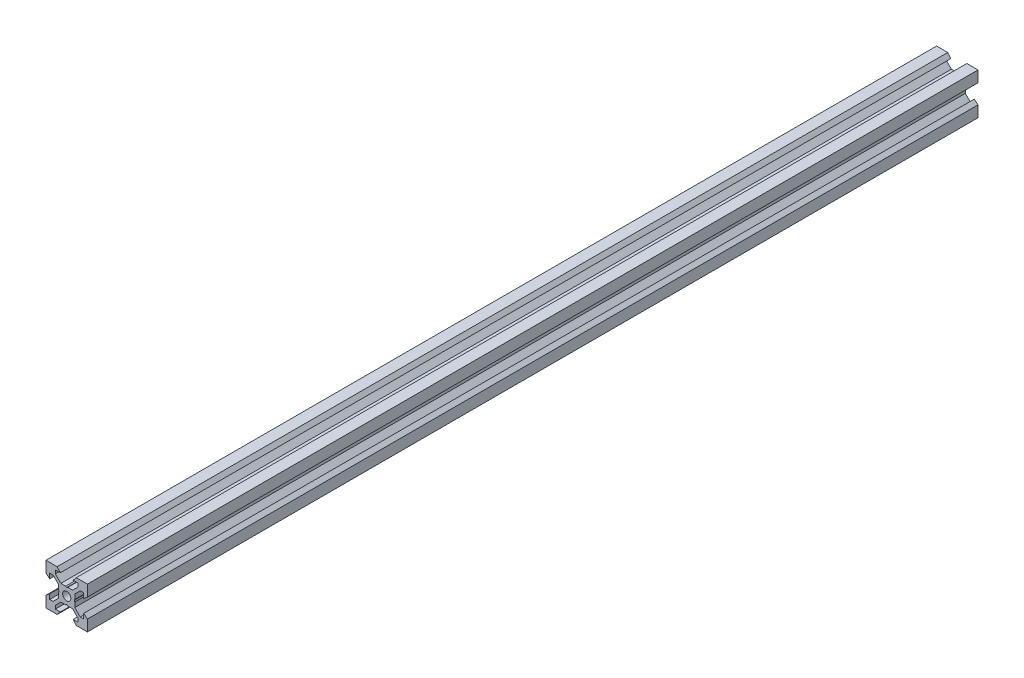
SolidWorks part; units mm, degrees
ref_plane "Front Plane" through (0, 0, 0) normal (0, 0, 1) x (1, 0, 0)
ref_plane "Top Plane" through (0, 0, 0) normal (0, 1, 0) x (1, 0, 0)
ref_plane "Right Plane" through (0, 0, 0) normal (1, 0, 0) x (0, 0, -1)
sketch "Sketch1" plane through (0, 0, 0) normal (0, 0, 1) x (1, 0, 0)
  line L0 (10, 10) -> (4.6104, 10) construction
  line L1 (10, 10) -> (10, 4.6104) construction
  line L2 (10, -10) -> (10, -4.6104) construction
  line L3 (10, -10) -> (4.6104, -10) construction
  line L4 (10, 10) -> (10, 4.6104)
  line L5 (6.5607, 5.5) -> (8.2, 5.5)
  line L6 (5.5, 8.2) -> (5.5, 6.5607)
  line L7 (10, 10) -> (4.6104, 10)
  line L8 (10, 10) -> (10, 4.6104)
  line L9 (6.5607, 5.5) -> (3.9, 2.8393)
  line L10 (5.5, 6.5607) -> (2.8393, 3.9)
  line L11 (10, 4.6104) -> (8.2, 3.1)
  line L12 (4.6104, 10) -> (3.1, 8.2)
  line L13 (8.2, 3.1) -> (8.2, 5.5)
  line L14 (3.1, 8.2) -> (5.5, 8.2)
  line L15 (-6.5607, 5.5) -> (-8.2, 5.5)
  line L16 (6.5607, -5.5) -> (8.2, -5.5)
  line L17 (3.1, -8.2) -> (5.5, -8.2)
  line L18 (8.2, -3.1) -> (8.2, -5.5)
  line L19 (4.6104, -10) -> (3.1, -8.2)
  line L20 (10, -4.6104) -> (8.2, -3.1)
  line L21 (0.5196, -3.9) -> (0, -3.6)
  line L22 (0.5196, 3.9) -> (0, 3.6)
  line L23 (3.6, 0) -> (3.9, -0.5196)
  line L24 (3.9, 0.5196) -> (3.6, 0)
  line L25 (3.9, 0.5196) -> (3.9, 2.8393)
  line L26 (2.8393, 3.9) -> (0.5196, 3.9)
  line L27 (3.9, -2.8393) -> (3.9, -0.5196)
  line L28 (2.8393, -3.9) -> (0.5196, -3.9)
  line L29 (5.5, -6.5607) -> (2.8393, -3.9)
  line L30 (6.5607, -5.5) -> (3.9, -2.8393)
  line L31 (10, -10) -> (10, -4.6104)
  line L32 (10, -10) -> (4.6104, -10)
  line L33 (5.5, -8.2) -> (5.5, -6.5607)
  line L34 (-6.5607, -5.5) -> (-8.2, -5.5)
  line L35 (10, -10) -> (10, -4.6104)
  line L36 (0, 0) -> (0, 8.2) construction
  line L37 (-10, -10) -> (-4.6104, -10) construction
  line L38 (-10, -10) -> (-10, -4.6104) construction
  line L39 (-10, 10) -> (-10, 4.6104) construction
  line L40 (-10, 10) -> (-4.6104, 10) construction
  line L41 (-10, -10) -> (-10, -4.6104)
  line L43 (-5.5, -8.2) -> (-5.5, -6.5607)
  line L44 (-10, -10) -> (-4.6104, -10)
  line L45 (-10, -10) -> (-10, -4.6104)
  line L46 (-6.5607, -5.5) -> (-3.9, -2.8393)
  line L47 (-5.5, -6.5607) -> (-2.8393, -3.9)
  line L48 (-2.8393, -3.9) -> (-0.5196, -3.9)
  line L49 (-3.9, -2.8393) -> (-3.9, -0.5196)
  line L50 (-2.8393, 3.9) -> (-0.5196, 3.9)
  line L51 (-3.9, 0.5196) -> (-3.9, 2.8393)
  line L52 (-3.9, 0.5196) -> (-3.6, 0)
  line L53 (-3.6, 0) -> (-3.9, -0.5196)
  line L54 (-0.5196, 3.9) -> (0, 3.6)
  line L55 (-0.5196, -3.9) -> (0, -3.6)
  line L56 (-10, -4.6104) -> (-8.2, -3.1)
  line L57 (-4.6104, -10) -> (-3.1, -8.2)
  line L58 (-8.2, -3.1) -> (-8.2, -5.5)
  line L59 (-3.1, -8.2) -> (-5.5, -8.2)
  line L60 (-10, -10) -> (10, -10) construction
  line L61 (-10, -10) -> (-10, 10) construction
  line L62 (-3.1, 8.2) -> (-5.5, 8.2)
  line L63 (-8.2, 3.1) -> (-8.2, 5.5)
  line L64 (-4.6104, 10) -> (-3.1, 8.2)
  line L65 (-10, 4.6104) -> (-8.2, 3.1)
  line L66 (-5.5, 6.5607) -> (-2.8393, 3.9)
  line L67 (-6.5607, 5.5) -> (-3.9, 2.8393)
  line L68 (-10, 10) -> (-10, 4.6104)
  line L69 (-10, 10) -> (-4.6104, 10)
  line L70 (-5.5, 8.2) -> (-5.5, 6.5607)
  line L71 (-10, 10) -> (10, 10) construction
  line L72 (-10, 10) -> (-10, 4.6104)
  line L73 (10, -10) -> (10, 10) construction
  line L74 (-10, -10) -> (10, 10) construction
  line L75 (-10, 10) -> (10, -10) construction
  circle A0 centre (0, 0) radius 2
  dimension "D7" = 4
  dimension "D1" = 20
  dimension "D2" = 5.3896
  dimension "D3" = 4.5
  dimension "D4" = 50
  dimension "D5" = 1.8
  dimension "D6" = 1.5104
  dimension "D8" = 5.5
  dimension "D9" = 120
  dimension "D10" = 0.3
  dimension "D11" = 2.3197
  dimension "D12" = 7.8
  dimension "D13" = 7.8
  dimension "D14" = 1.5
  dimension "D15" = 2.6607
extrude "Boss-Extrude1" add sketch "Sketch1" along normal mid plane 430 contours L70 L62 L64 L69 L68 L65 L63 L15 L67 L51 L52 L53 L49 L46 L34 L58 L56 L41 L44 L57 L59 L43 L47 L48 L55 L21 L28 L29 L33 L17 L19 L32 L31 L20 L18 L16 L30 L27 L23 L24 L25 L9 L5 L13 L11 L4 L7 L12 L14 L6 L10
